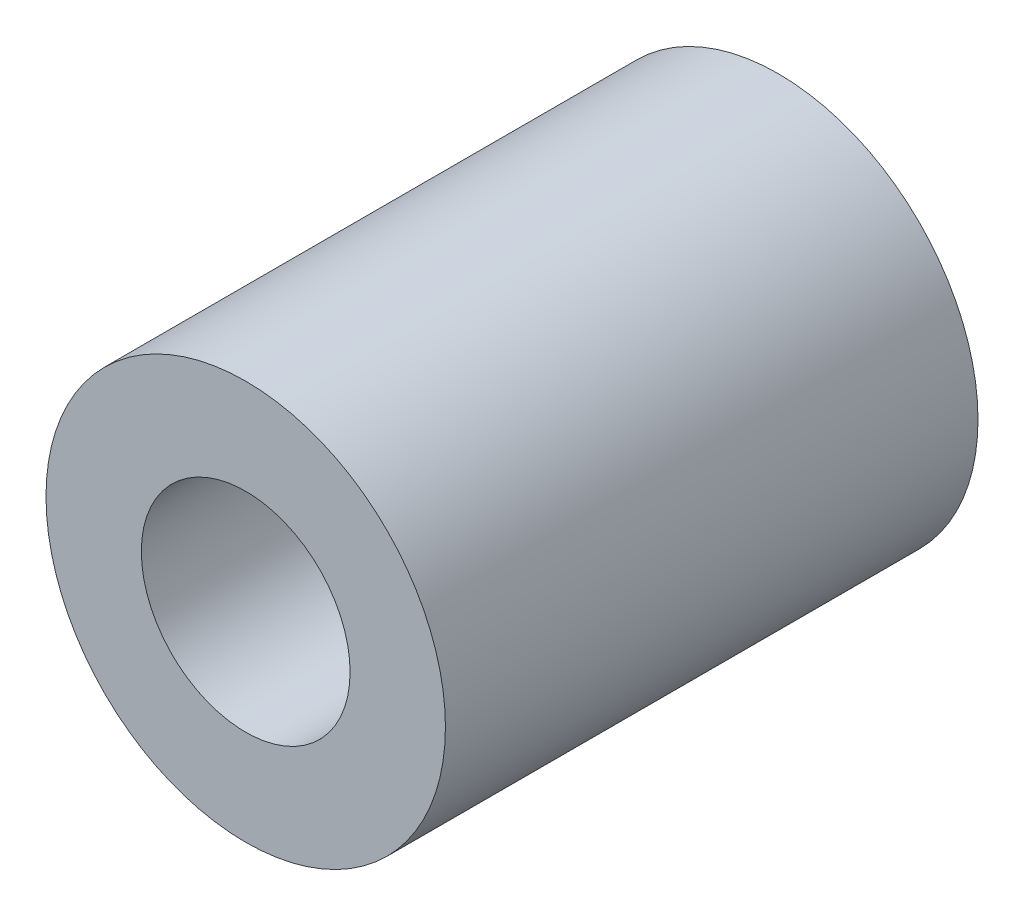
SolidWorks part; units mm, degrees
ref_plane "Front Plane" through (0, 0, 0) normal (0, 0, 1) x (1, 0, 0)
ref_plane "Top Plane" through (0, 0, 0) normal (0, 1, 0) x (1, 0, 0)
ref_plane "Right Plane" through (0, 0, 0) normal (1, 0, 0) x (0, 0, -1)
sketch "Sketch1" plane through (0, 0, 0) normal (0, 0, 1) x (1, 0, 0)
  circle A0 centre (0, 0) radius 4.7625
  circle A1 centre (0, 0) radius 2.4892
  dimension "D1" = 9.525
  dimension "D2" = 4.9784
extrude "Boss-Extrude1" add sketch "Sketch1" along normal mid plane 12.7
